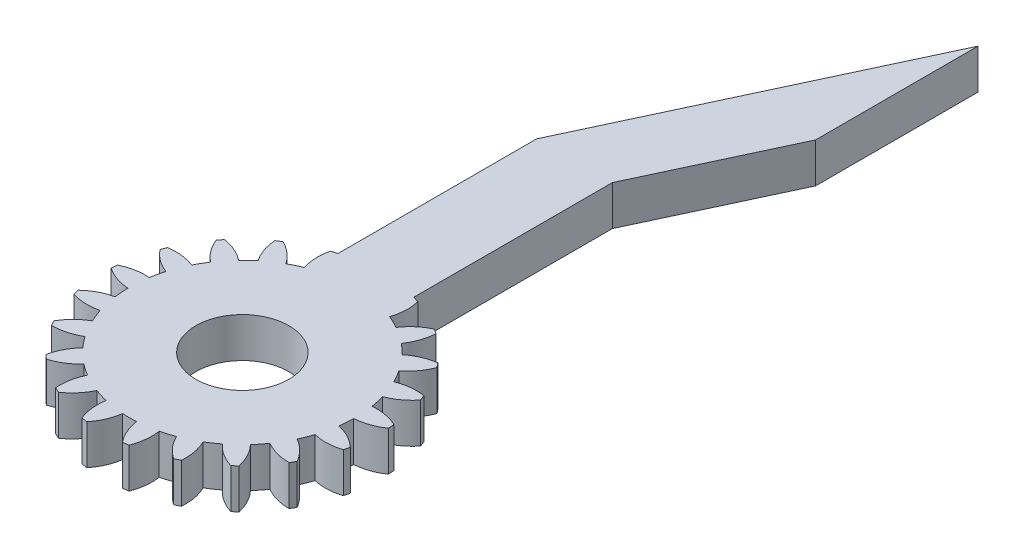
SolidWorks part; units mm, degrees
ref_plane "Front Plane" through (0, 0, 0) normal (0, 0, 1) x (1, 0, 0)
ref_plane "Top Plane" through (0, 0, 0) normal (0, 1, 0) x (1, 0, 0)
ref_plane "Right Plane" through (0, 0, 0) normal (1, 0, 0) x (0, 0, -1)
sketch "Sketch1" plane through (0, 0, 0) normal (0, 1, 0) x (1, 0, 0)
  line L0 (0, 10.45) -> (0, -10.45) construction
  line L31 (0.22, 10.45) -> (-0.22, 10.45)
  line L32 (3.2904, 9.9209) -> (2.87, 10.0506)
  line L33 (6.0685, 8.5103) -> (5.7049, 8.7581)
  line L34 (8.3073, 6.3435) -> (8.033, 6.6875)
  line L35 (9.808, 3.613) -> (9.6473, 4.0226)
  line L36 (10.4372, 0.5615) -> (10.4043, 1.0003)
  line L37 (10.139, -2.5398) -> (10.237, -2.1109)
  line L38 (8.94, -5.4155) -> (9.16, -5.0345)
  line L39 (6.9465, -7.81) -> (7.2691, -7.5108)
  line L40 (4.3359, -9.5106) -> (4.7323, -9.3197)
  line L41 (1.3399, -10.3661) -> (1.775, -10.3005)
  line L42 (-1.775, -10.3005) -> (-1.3399, -10.3661)
  line L43 (-4.7323, -9.3197) -> (-4.3359, -9.5106)
  line L44 (-7.2691, -7.5108) -> (-6.9465, -7.81)
  line L45 (-9.16, -5.0345) -> (-8.94, -5.4155)
  line L46 (-10.237, -2.1109) -> (-10.139, -2.5398)
  line L47 (-10.4043, 1.0003) -> (-10.4372, 0.5615)
  line L48 (-9.6473, 4.0226) -> (-9.808, 3.613)
  line L49 (-8.033, 6.6875) -> (-8.3073, 6.3435)
  line L50 (-5.7049, 8.7581) -> (-6.0685, 8.5103)
  line L51 (-2.87, 10.0506) -> (-3.2904, 9.9209)
  circle A0 centre (0, 0) radius 3.5
  arc A73 (-3.2123, 7.8696) -> (-4.1499, 7.4181) centre (0, 0) ccw
  arc A75 (-0.75, 8.4668) -> (-0.22, 10.45) centre (3.0999, 8.5004) cw
  arc A77 (0.75, 8.4668) -> (0.22, 10.45) centre (-3.0999, 8.5004) ccw
  arc A79 (1.779, 8.3118) -> (2.87, 10.0506) centre (5.4677, 7.209) cw
  arc A81 (3.2123, 7.8696) -> (3.2904, 9.9209) centre (-0.4566, 9.0364) ccw
  arc A83 (4.1499, 7.4181) -> (5.7049, 8.7581) centre (7.3496, 5.2771) cw
  arc A85 (5.3892, 6.5731) -> (6.0685, 8.5103) centre (2.2272, 8.7695) ccw
  arc A86 (6.152, 5.8654) -> (8.033, 6.6875) centre (8.5786, 2.8763) cw
  arc A87 (7.0873, 4.6926) -> (8.3073, 6.3435) centre (4.7131, 7.7235) ccw
  arc A88 (7.6076, 3.7914) -> (9.6473, 4.0226) centre (9.0453, 0.22) cw
  arc A89 (8.1556, 2.3951) -> (9.808, 3.613) centre (6.7803, 5.9911) ccw
  arc A90 (8.3871, 1.3806) -> (10.4043, 1.0003) centre (8.7083, -2.456) cw
  arc A91 (8.4992, -0.1152) -> (10.4372, 0.5615) centre (8.2449, 3.7264) ccw
  arc A92 (8.4215, -1.1529) -> (10.237, -2.1109) centre (7.5975, -4.9136) cw
  arc A93 (8.0877, -2.6152) -> (10.139, -2.5398) centre (8.977, 1.1306) ccw
  arc A94 (7.7075, -3.5839) -> (9.16, -5.0345) centre (5.8116, -6.9347) cw
  arc A95 (6.9575, -4.8829) -> (8.94, -5.4155) centre (8.9115, -1.5656) ccw
  arc A96 (6.3087, -5.6965) -> (7.2691, -7.5108) centre (3.5094, -8.3396) cw
  arc A97 (5.2091, -6.7168) -> (6.9465, -7.81) centre (8.0541, -4.1228) ccw
  arc A98 (4.3494, -7.303) -> (4.7323, -9.3197) centre (0.8953, -9.0035) cw
  arc A99 (2.9979, -7.9538) -> (4.3359, -9.5106) centre (6.481, -6.3136) ccw
  arc A100 (2.0035, -8.2605) -> (1.775, -10.3005) centre (-1.7983, -8.8674) cw
  arc A101 (0.5203, -8.4841) -> (1.3399, -10.3661) centre (4.3321, -7.9434) ccw
  arc A102 (-0.5203, -8.4841) -> (-1.3399, -10.3661) centre (-4.3321, -7.9434) cw
  arc A103 (-2.0035, -8.2605) -> (-1.775, -10.3005) centre (1.7983, -8.8674) ccw
  arc A104 (-2.9979, -7.9538) -> (-4.3359, -9.5106) centre (-6.481, -6.3136) cw
  arc A105 (-4.3494, -7.303) -> (-4.7323, -9.3197) centre (-0.8953, -9.0035) ccw
  arc A106 (-5.2091, -6.7168) -> (-6.9465, -7.81) centre (-8.0541, -4.1228) cw
  arc A107 (-6.3087, -5.6965) -> (-7.2691, -7.5108) centre (-3.5094, -8.3396) ccw
  arc A108 (-6.9575, -4.8829) -> (-8.94, -5.4155) centre (-8.9115, -1.5656) cw
  arc A109 (-7.7075, -3.5839) -> (-9.16, -5.0345) centre (-5.8116, -6.9347) ccw
  arc A110 (-8.0877, -2.6152) -> (-10.139, -2.5398) centre (-8.977, 1.1306) cw
  arc A111 (-8.4215, -1.1529) -> (-10.237, -2.1109) centre (-7.5975, -4.9136) ccw
  arc A112 (-8.4992, -0.1152) -> (-10.4372, 0.5615) centre (-8.2449, 3.7264) cw
  arc A113 (-8.3871, 1.3806) -> (-10.4043, 1.0003) centre (-8.7083, -2.456) ccw
  arc A114 (-8.1556, 2.3951) -> (-9.808, 3.613) centre (-6.7803, 5.9911) cw
  arc A115 (-7.6076, 3.7914) -> (-9.6473, 4.0226) centre (-9.0453, 0.22) ccw
  arc A116 (-7.0873, 4.6926) -> (-8.3073, 6.3435) centre (-4.7131, 7.7235) cw
  arc A117 (-6.152, 5.8654) -> (-8.033, 6.6875) centre (-8.5786, 2.8763) ccw
  arc A118 (-5.3892, 6.5731) -> (-6.0685, 8.5103) centre (-2.2272, 8.7695) cw
  arc A119 (-4.1499, 7.4181) -> (-5.7049, 8.7581) centre (-7.3496, 5.2771) ccw
  arc A120 (-3.2123, 7.8696) -> (-3.2904, 9.9209) centre (0.4566, 9.0364) cw
  arc A121 (-1.779, 8.3118) -> (-2.87, 10.0506) centre (-5.4677, 7.209) ccw
  arc A122 (1.779, 8.3118) -> (0.75, 8.4668) centre (0, 0) ccw
  arc A123 (-0.75, 8.4668) -> (-1.779, 8.3118) centre (0, 0) ccw
  arc A124 (4.1499, 7.4181) -> (3.2123, 7.8696) centre (0, 0) ccw
  arc A125 (6.152, 5.8654) -> (5.3892, 6.5731) centre (0, 0) ccw
  arc A126 (7.6076, 3.7914) -> (7.0873, 4.6926) centre (0, 0) ccw
  arc A127 (8.3871, 1.3806) -> (8.1556, 2.3951) centre (0, 0) ccw
  arc A128 (8.4215, -1.1529) -> (8.4992, -0.1152) centre (0, 0) ccw
  arc A129 (7.7075, -3.5839) -> (8.0877, -2.6152) centre (0, 0) ccw
  arc A130 (6.3087, -5.6965) -> (6.9575, -4.8829) centre (0, 0) ccw
  arc A131 (4.3494, -7.303) -> (5.2091, -6.7168) centre (0, 0) ccw
  arc A132 (2.0035, -8.2605) -> (2.9979, -7.9538) centre (0, 0) ccw
  arc A133 (-0.5203, -8.4841) -> (0.5203, -8.4841) centre (0, 0) ccw
  arc A134 (-2.9979, -7.9538) -> (-2.0035, -8.2605) centre (0, 0) ccw
  arc A135 (-5.2091, -6.7168) -> (-4.3494, -7.303) centre (0, 0) ccw
  arc A136 (-6.9575, -4.8829) -> (-6.3087, -5.6965) centre (0, 0) ccw
  arc A137 (-8.0877, -2.6152) -> (-7.7075, -3.5839) centre (0, 0) ccw
  arc A138 (-8.4992, -0.1152) -> (-8.4215, -1.1529) centre (0, 0) ccw
  arc A139 (-8.1556, 2.3951) -> (-8.3871, 1.3806) centre (0, 0) ccw
  arc A140 (-7.0873, 4.6926) -> (-7.6076, 3.7914) centre (0, 0) ccw
  arc A141 (-5.3892, 6.5731) -> (-6.152, 5.8654) centre (0, 0) ccw
  point P8 (0, 0)
  point P136 (0, 0)
  dimension "D1" = 7
  dimension "D2" = 17
  dimension "D5" = 0.75
  dimension "D6" = 3.85
  dimension "D3" = 20.9
  dimension "D4" = 0.22
  dimension "D7" = 21
extrude "Boss-Extrude1" add sketch "Sketch1" along normal blind 3
sketch "Sketch4" plane through (0, 3, 0) normal (0, 1, 0) x (1, 0, 0)
  line L0 (-2.85, 4.2578) -> (-2.85, 25)
  line L1 (-2.85, 25) -> (7.7155, 47.6577)
  line L2 (7.7155, 47.6577) -> (7.7155, 35.434)
  line L3 (7.7155, 35.434) -> (2.85, 25)
  line L4 (2.85, 25) -> (2.85, 4.2578)
  line L5 (0, -0.3781) -> (0, 31.2718) construction
  line L6 (-2.85, 4.2578) -> (2.85, 4.2578)
  dimension "D1" = 5.7
  dimension "D2" = 155
  dimension "D3" = 25
  dimension "D4" = 25
extrude "Boss-Extrude2" add sketch "Sketch4" against normal up to surface (3 mm away) up to face at (0, 0, 0)
